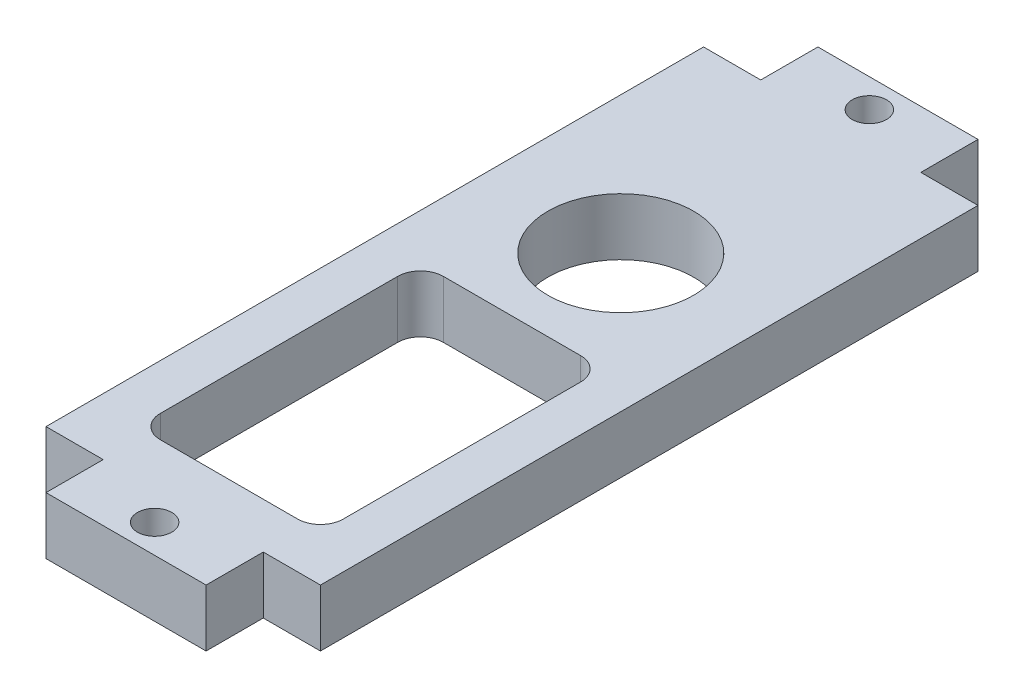
SolidWorks part; units mm, degrees
ref_plane "Front Plane" through (0, 0, 0) normal (0, 0, 1) x (1, 0, 0)
ref_plane "Top Plane" through (0, 0, 0) normal (0, 1, 0) x (1, 0, 0)
ref_plane "Right Plane" through (0, 0, 0) normal (1, 0, 0) x (0, 0, -1)
sketch "Sketch1" plane through (0, 0, 0) normal (0, 1, 0) x (1, 0, 0)
  line L0 (12, 53.5) -> (12, 0) construction
  line L1 (5, -14) -> (19, -14)
  line L2 (0, -9) -> (0, 48.5)
  line L3 (5, 53.5) -> (19, 53.5)
  line L4 (24, -9) -> (24, 48.5)
  line L5 (0, 19.75) -> (20, 19.75) construction
  line L6 (24, 48.5) -> (19, 48.5)
  line L9 (0, 48.5) -> (5, 48.5)
  line L10 (5, 53.5) -> (5, 48.5)
  line L11 (19, 53.5) -> (19, 48.5)
  line L15 (19, -14) -> (19, -9)
  line L16 (24, -9) -> (19, -9)
  line L18 (0, -9) -> (5, -9)
  line L19 (5, -14) -> (5, -9)
  circle A0 centre (12, 51) radius 1.5
  circle A1 centre (12, -11.5) radius 1.5
  dimension "D3" = 3
  dimension "D4" = 2.5
  dimension "D1" = 67.5
  dimension "D2" = 24
  dimension "D5" = 5
  dimension "D6" = 5
extrude "Boss-Extrude1" add sketch "Sketch1" along normal blind 5
sketch "Sketch2" plane through (0, 5, 0) normal (0, 1, 0) x (1, 0, 0)
  line L0 (12, 53.5) -> (12, -14) construction
  line L1 (19, 53.5) -> (5, 53.5) construction
  line L2 (5, -14) -> (19, -14) construction
  circle A0 centre (12, 29.26) radius 6.375
  circle A1 centre (12, 51) radius 1.5 construction
  dimension "D1" = 21.74
  dimension "D2" = 12.75
extrude "Cut-Extrude1" cut sketch "Sketch2" against normal blind 10
sketch "Sketch3" plane through (0, 5, 0) normal (0, 1, 0) x (1, 0, 0)
  line L0 (4, -5) -> (20, -5) construction
  line L1 (20, -5) -> (20, 44.5) construction
  line L2 (20, 44.5) -> (4, 44.5) construction
  line L3 (4, 44.5) -> (4, -5) construction
  line L4 (0, 48.5) -> (0, -9) construction
  line L5 (12, 22.885) -> (12, 35.635) construction
  line L7 (0, -9) -> (5, -9) construction
  line L8 (5, 48.5) -> (0, 48.5) construction
  line L10 (4, -5) -> (20, -5)
  line L12 (4, -5) -> (20, -5)
  line L13 (4, -5) -> (4, 19.75)
  line L14 (4, 19.75) -> (20, 19.75)
  line L15 (20, -5) -> (20, 19.75)
  circle A0 centre (12, 29.26) radius 6.375 construction
  dimension "D1" = 4
  dimension "D3" = 4
  dimension "D4" = 4
extrude "Cut-Extrude2" cut sketch "Sketch3" against normal blind 10 contours L10 L15 L14 L13
fillet "Fillet1" radius 2 4 edges at (20, 2.5, 5) (4, 2.5, 5) (4, 2.5, -19.75) (20, 2.5, -19.75)
